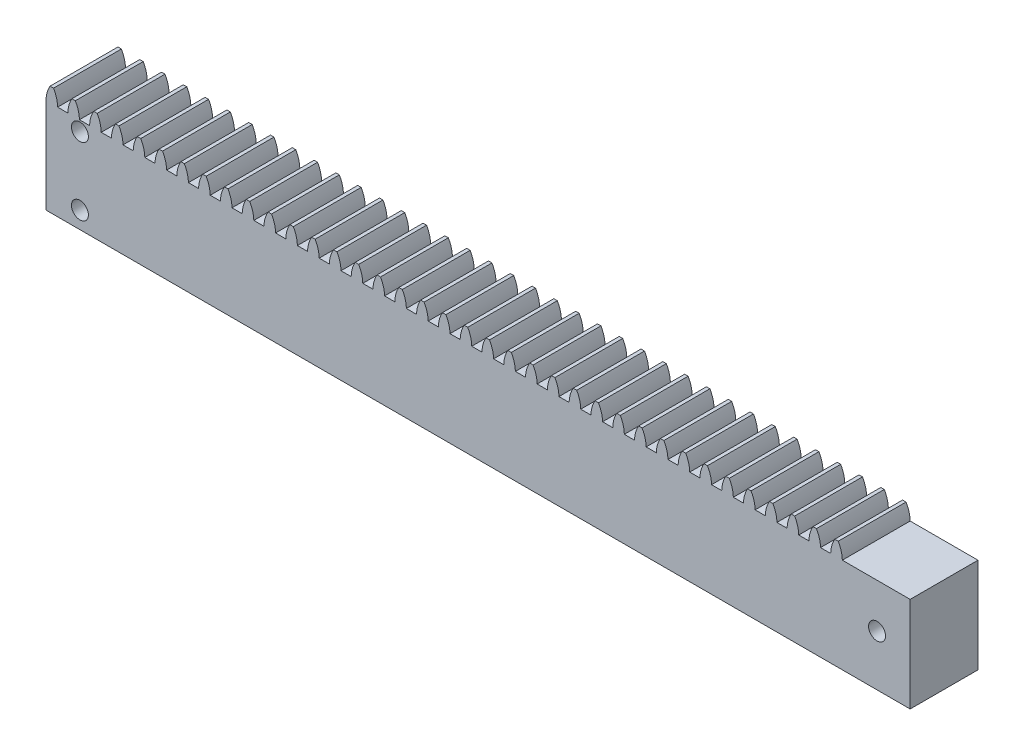
SolidWorks part; units mm, degrees
material "自訂玻璃纖維"
ref_plane "前基準面" through (0, 0, 0) normal (0, 0, 1) x (1, 0, 0)
ref_plane "上基準面" through (0, 0, 0) normal (0, 1, 0) x (1, 0, 0)
ref_plane "右基準面" through (0, 0, 0) normal (1, 0, 0) x (0, 0, -1)
sketch "草圖2" plane through (-38.6801, 0, 0) normal (0, 0, 1) x (1, 0, 0)
  line L0 (1.0493, 17.4015) -> (1.5623, 17.4015)
  line L1 (2.1626, 15.2764) -> (3.6621, 15.2764)
  line L2 (5.3756, 15.2764) -> (6.8752, 15.2764)
  line L3 (4.2623, 17.4015) -> (4.7754, 17.4015)
  line L4 (7.4754, 17.4015) -> (7.9884, 17.4015)
  line L5 (8.5886, 15.2764) -> (10.0882, 15.2764)
  line L6 (11.8017, 15.2764) -> (13.3012, 15.2764)
  line L7 (10.6884, 17.4015) -> (11.2014, 17.4015)
  line L8 (13.9014, 17.4015) -> (14.4145, 17.4015)
  line L9 (15.0147, 15.2764) -> (16.5143, 15.2764)
  line L10 (18.2277, 15.2764) -> (19.7273, 15.2764)
  line L11 (17.1145, 17.4015) -> (17.6275, 17.4015)
  line L12 (20.3275, 17.4015) -> (20.8405, 17.4015)
  line L13 (21.4408, 15.2764) -> (22.9403, 15.2764)
  line L14 (24.6538, 15.2764) -> (26.1534, 15.2764)
  line L15 (23.5405, 17.4015) -> (24.0536, 17.4015)
  line L16 (26.7536, 17.4015) -> (27.2666, 17.4015)
  line L17 (27.8668, 15.2764) -> (29.3664, 15.2764)
  line L18 (31.0799, 15.2764) -> (32.5794, 15.2764)
  line L19 (29.9666, 17.4015) -> (30.4797, 17.4015)
  line L20 (33.1797, 17.4015) -> (33.6927, 17.4015)
  line L21 (34.2929, 15.2764) -> (35.7925, 15.2764)
  line L22 (37.5059, 15.2764) -> (39.0055, 15.2764)
  line L23 (36.3927, 17.4015) -> (36.9057, 17.4015)
  line L24 (39.6057, 17.4015) -> (40.1188, 17.4015)
  line L25 (40.719, 15.2764) -> (42.2185, 15.2764)
  line L26 (43.932, 15.2764) -> (45.4316, 15.2764)
  line L27 (42.8188, 17.4015) -> (43.3318, 17.4015)
  line L28 (46.0318, 17.4015) -> (46.5448, 17.4015)
  line L29 (47.145, 15.2764) -> (48.6446, 15.2764)
  line L30 (50.3581, 15.2764) -> (51.8576, 15.2764)
  line L31 (49.2448, 17.4015) -> (49.7579, 17.4015)
  line L32 (52.4579, 17.4015) -> (52.9709, 17.4015)
  line L33 (53.5711, 15.2764) -> (55.0707, 15.2764)
  line L34 (56.7841, 15.2764) -> (58.2837, 15.2764)
  line L35 (55.6709, 17.4015) -> (56.1839, 17.4015)
  line L36 (58.8839, 17.4015) -> (59.397, 17.4015)
  line L37 (59.9972, 15.2764) -> (61.4967, 15.2764)
  line L38 (63.2102, 15.2764) -> (64.7098, 15.2764)
  line L39 (62.097, 17.4015) -> (62.61, 17.4015)
  line L40 (65.31, 17.4015) -> (65.823, 17.4015)
  line L41 (66.4233, 15.2764) -> (67.9228, 15.2764)
  line L42 (69.6363, 15.2764) -> (71.1358, 15.2764)
  line L43 (68.523, 17.4015) -> (69.0361, 17.4015)
  line L44 (71.7361, 17.4015) -> (72.2491, 17.4015)
  line L45 (72.8493, 15.2764) -> (74.3489, 15.2764)
  line L46 (76.0624, 15.2764) -> (77.5619, 15.2764)
  line L47 (74.9491, 17.4015) -> (75.4621, 17.4015)
  line L48 (78.1621, 17.4015) -> (78.6752, 17.4015)
  line L49 (79.2754, 15.2764) -> (80.7749, 15.2764)
  line L50 (82.4884, 15.2764) -> (83.988, 15.2764)
  line L51 (81.3752, 17.4015) -> (81.8882, 17.4015)
  line L52 (84.5882, 17.4015) -> (85.1012, 17.4015)
  line L53 (85.7015, 15.2764) -> (87.201, 15.2764)
  line L54 (88.9145, 15.2764) -> (90.414, 15.2764)
  line L55 (87.8012, 17.4015) -> (88.3143, 17.4015)
  line L56 (91.0143, 17.4015) -> (91.5273, 17.4015)
  line L57 (92.1275, 15.2764) -> (93.6271, 15.2764)
  line L58 (95.3406, 15.2764) -> (96.8401, 15.2764)
  line L59 (94.2273, 17.4015) -> (94.7403, 17.4015)
  line L60 (97.4403, 17.4015) -> (97.9534, 17.4015)
  line L61 (98.5536, 15.2764) -> (100.0532, 15.2764)
  line L62 (101.7666, 15.2764) -> (103.2662, 15.2764)
  line L63 (100.6534, 17.4015) -> (101.1664, 17.4015)
  line L64 (103.8664, 17.4015) -> (104.3794, 17.4015)
  line L65 (104.9797, 15.2764) -> (106.4792, 15.2764)
  line L66 (108.1927, 15.2764) -> (109.6923, 15.2764)
  line L67 (107.0794, 17.4015) -> (107.5925, 17.4015)
  line L68 (110.2925, 17.4015) -> (110.8055, 17.4015)
  line L69 (111.4057, 15.2764) -> (112.9053, 15.2764)
  line L70 (114.6188, 15.2764) -> (116.1183, 15.2764)
  line L71 (113.5055, 17.4015) -> (114.0185, 17.4015)
  line L72 (116.7185, 17.4015) -> (117.2316, 17.4015)
  line L73 (117.8318, 15.2764) -> (127.8318, 15.2764)
  line L74 (127.8318, 15.2764) -> (127.8318, 1.2764)
  line L75 (127.8318, 1.2764) -> (0.4491, 1.2764)
  line L76 (0.4491, 1.2764) -> (0.4491, 15.2764)
  arc A0 (2.1626, 15.2764) -> (1.5623, 17.4015) centre (-2.2949, 15.1647) ccw
  arc A1 (0.4491, 15.2764) -> (1.0493, 17.4015) centre (4.9065, 15.1647) cw
  arc A2 (5.3756, 15.2764) -> (4.7754, 17.4015) centre (0.9182, 15.1647) ccw
  arc A3 (3.6621, 15.2764) -> (4.2623, 17.4015) centre (8.1195, 15.1647) cw
  arc A4 (10.0882, 15.2764) -> (10.6884, 17.4015) centre (14.5456, 15.1647) cw
  arc A5 (8.5886, 15.2764) -> (7.9884, 17.4015) centre (4.1312, 15.1647) ccw
  arc A6 (6.8752, 15.2764) -> (7.4754, 17.4015) centre (11.3326, 15.1647) cw
  arc A7 (11.8017, 15.2764) -> (11.2014, 17.4015) centre (7.3442, 15.1647) ccw
  arc A8 (16.5143, 15.2764) -> (17.1145, 17.4015) centre (20.9717, 15.1647) cw
  arc A9 (15.0147, 15.2764) -> (14.4145, 17.4015) centre (10.5573, 15.1647) ccw
  arc A10 (13.3012, 15.2764) -> (13.9014, 17.4015) centre (17.7587, 15.1647) cw
  arc A11 (18.2277, 15.2764) -> (17.6275, 17.4015) centre (13.7703, 15.1647) ccw
  arc A12 (22.9403, 15.2764) -> (23.5405, 17.4015) centre (27.3978, 15.1647) cw
  arc A13 (21.4408, 15.2764) -> (20.8405, 17.4015) centre (16.9833, 15.1647) ccw
  arc A14 (19.7273, 15.2764) -> (20.3275, 17.4015) centre (24.1847, 15.1647) cw
  arc A15 (24.6538, 15.2764) -> (24.0536, 17.4015) centre (20.1964, 15.1647) ccw
  arc A16 (29.3664, 15.2764) -> (29.9666, 17.4015) centre (33.8238, 15.1647) cw
  arc A17 (27.8668, 15.2764) -> (27.2666, 17.4015) centre (23.4094, 15.1647) ccw
  arc A18 (26.1534, 15.2764) -> (26.7536, 17.4015) centre (30.6108, 15.1647) cw
  arc A19 (31.0799, 15.2764) -> (30.4797, 17.4015) centre (26.6224, 15.1647) ccw
  arc A20 (35.7925, 15.2764) -> (36.3927, 17.4015) centre (40.2499, 15.1647) cw
  arc A21 (34.2929, 15.2764) -> (33.6927, 17.4015) centre (29.8355, 15.1647) ccw
  arc A22 (32.5794, 15.2764) -> (33.1797, 17.4015) centre (37.0369, 15.1647) cw
  arc A23 (37.5059, 15.2764) -> (36.9057, 17.4015) centre (33.0485, 15.1647) ccw
  arc A24 (42.2185, 15.2764) -> (42.8188, 17.4015) centre (46.676, 15.1647) cw
  arc A25 (40.719, 15.2764) -> (40.1188, 17.4015) centre (36.2615, 15.1647) ccw
  arc A26 (39.0055, 15.2764) -> (39.6057, 17.4015) centre (43.4629, 15.1647) cw
  arc A27 (43.932, 15.2764) -> (43.3318, 17.4015) centre (39.4746, 15.1647) ccw
  arc A28 (48.6446, 15.2764) -> (49.2448, 17.4015) centre (53.102, 15.1647) cw
  arc A29 (47.145, 15.2764) -> (46.5448, 17.4015) centre (42.6876, 15.1647) ccw
  arc A30 (45.4316, 15.2764) -> (46.0318, 17.4015) centre (49.889, 15.1647) cw
  arc A31 (50.3581, 15.2764) -> (49.7579, 17.4015) centre (45.9007, 15.1647) ccw
  arc A32 (55.0707, 15.2764) -> (55.6709, 17.4015) centre (59.5281, 15.1647) cw
  arc A33 (53.5711, 15.2764) -> (52.9709, 17.4015) centre (49.1137, 15.1647) ccw
  arc A34 (51.8576, 15.2764) -> (52.4579, 17.4015) centre (56.3151, 15.1647) cw
  arc A35 (56.7841, 15.2764) -> (56.1839, 17.4015) centre (52.3267, 15.1647) ccw
  arc A36 (61.4967, 15.2764) -> (62.097, 17.4015) centre (65.9542, 15.1647) cw
  arc A37 (59.9972, 15.2764) -> (59.397, 17.4015) centre (55.5398, 15.1647) ccw
  arc A38 (58.2837, 15.2764) -> (58.8839, 17.4015) centre (62.7411, 15.1647) cw
  arc A39 (63.2102, 15.2764) -> (62.61, 17.4015) centre (58.7528, 15.1647) ccw
  arc A40 (67.9228, 15.2764) -> (68.523, 17.4015) centre (72.3802, 15.1647) cw
  arc A41 (66.4233, 15.2764) -> (65.823, 17.4015) centre (61.9658, 15.1647) ccw
  arc A42 (64.7098, 15.2764) -> (65.31, 17.4015) centre (69.1672, 15.1647) cw
  arc A43 (69.6363, 15.2764) -> (69.0361, 17.4015) centre (65.1789, 15.1647) ccw
  arc A44 (74.3489, 15.2764) -> (74.9491, 17.4015) centre (78.8063, 15.1647) cw
  arc A45 (72.8493, 15.2764) -> (72.2491, 17.4015) centre (68.3919, 15.1647) ccw
  arc A46 (71.1358, 15.2764) -> (71.7361, 17.4015) centre (75.5933, 15.1647) cw
  arc A47 (76.0624, 15.2764) -> (75.4621, 17.4015) centre (71.6049, 15.1647) ccw
  arc A48 (80.7749, 15.2764) -> (81.3752, 17.4015) centre (85.2324, 15.1647) cw
  arc A49 (79.2754, 15.2764) -> (78.6752, 17.4015) centre (74.818, 15.1647) ccw
  arc A50 (77.5619, 15.2764) -> (78.1621, 17.4015) centre (82.0193, 15.1647) cw
  arc A51 (82.4884, 15.2764) -> (81.8882, 17.4015) centre (78.031, 15.1647) ccw
  arc A52 (87.201, 15.2764) -> (87.8012, 17.4015) centre (91.6584, 15.1647) cw
  arc A53 (85.7015, 15.2764) -> (85.1012, 17.4015) centre (81.244, 15.1647) ccw
  arc A54 (83.988, 15.2764) -> (84.5882, 17.4015) centre (88.4454, 15.1647) cw
  arc A55 (88.9145, 15.2764) -> (88.3143, 17.4015) centre (84.4571, 15.1647) ccw
  arc A56 (93.6271, 15.2764) -> (94.2273, 17.4015) centre (98.0845, 15.1647) cw
  arc A57 (92.1275, 15.2764) -> (91.5273, 17.4015) centre (87.6701, 15.1647) ccw
  arc A58 (90.414, 15.2764) -> (91.0143, 17.4015) centre (94.8715, 15.1647) cw
  arc A59 (95.3406, 15.2764) -> (94.7403, 17.4015) centre (90.8831, 15.1647) ccw
  arc A60 (100.0532, 15.2764) -> (100.6534, 17.4015) centre (104.5106, 15.1647) cw
  arc A61 (98.5536, 15.2764) -> (97.9534, 17.4015) centre (94.0962, 15.1647) ccw
  arc A62 (96.8401, 15.2764) -> (97.4403, 17.4015) centre (101.2975, 15.1647) cw
  arc A63 (101.7666, 15.2764) -> (101.1664, 17.4015) centre (97.3092, 15.1647) ccw
  arc A64 (106.4792, 15.2764) -> (107.0794, 17.4015) centre (110.9366, 15.1647) cw
  arc A65 (104.9797, 15.2764) -> (104.3794, 17.4015) centre (100.5222, 15.1647) ccw
  arc A66 (103.2662, 15.2764) -> (103.8664, 17.4015) centre (107.7236, 15.1647) cw
  arc A67 (108.1927, 15.2764) -> (107.5925, 17.4015) centre (103.7353, 15.1647) ccw
  arc A68 (112.9053, 15.2764) -> (113.5055, 17.4015) centre (117.3627, 15.1647) cw
  arc A69 (111.4057, 15.2764) -> (110.8055, 17.4015) centre (106.9483, 15.1647) ccw
  arc A70 (109.6923, 15.2764) -> (110.2925, 17.4015) centre (114.1497, 15.1647) cw
  arc A71 (114.6188, 15.2764) -> (114.0185, 17.4015) centre (110.1613, 15.1647) ccw
  arc A73 (117.8318, 15.2764) -> (117.2316, 17.4015) centre (113.3744, 15.1647) ccw
  arc A74 (116.1183, 15.2764) -> (116.7185, 17.4015) centre (120.5758, 15.1647) cw
  point P18 (1.0493, 17.4015)
  point P19 (1.5623, 17.4015)
  point P20 (0.4491, 15.2764)
  point P21 (2.1626, 15.2764)
  point P22 (127.8318, 15.2764)
  point P31 (7.4754, 17.4015)
  point P32 (7.9884, 17.4015)
  point P33 (6.8752, 15.2764)
  point P34 (8.5886, 15.2764)
  point P48 (13.9014, 17.4015)
  point P49 (14.4145, 17.4015)
  point P50 (13.3012, 15.2764)
  point P51 (15.0147, 15.2764)
  point P65 (20.3275, 17.4015)
  point P66 (20.8405, 17.4015)
  point P67 (19.7273, 15.2764)
  point P68 (21.4408, 15.2764)
  point P82 (26.7536, 17.4015)
  point P83 (27.2666, 17.4015)
  point P84 (26.1534, 15.2764)
  point P85 (27.8668, 15.2764)
  point P99 (33.1797, 17.4015)
  point P100 (33.6927, 17.4015)
  point P101 (32.5794, 15.2764)
  point P102 (34.2929, 15.2764)
  point P116 (39.6057, 17.4015)
  point P117 (40.1188, 17.4015)
  point P118 (39.0055, 15.2764)
  point P119 (40.719, 15.2764)
  point P133 (46.0318, 17.4015)
  point P134 (46.5448, 17.4015)
  point P135 (45.4316, 15.2764)
  point P136 (47.145, 15.2764)
  point P150 (52.4579, 17.4015)
  point P151 (52.9709, 17.4015)
  point P152 (51.8576, 15.2764)
  point P153 (53.5711, 15.2764)
  point P167 (58.8839, 17.4015)
  point P168 (59.397, 17.4015)
  point P169 (58.2837, 15.2764)
  point P170 (59.9972, 15.2764)
  point P184 (65.31, 17.4015)
  point P185 (65.823, 17.4015)
  point P186 (64.7098, 15.2764)
  point P187 (66.4233, 15.2764)
  point P201 (71.7361, 17.4015)
  point P202 (72.2491, 17.4015)
  point P203 (71.1358, 15.2764)
  point P204 (72.8493, 15.2764)
  point P218 (78.1621, 17.4015)
  point P219 (78.6752, 17.4015)
  point P220 (77.5619, 15.2764)
  point P221 (79.2754, 15.2764)
  point P235 (84.5882, 17.4015)
  point P236 (85.1012, 17.4015)
  point P237 (83.988, 15.2764)
  point P238 (85.7015, 15.2764)
  point P252 (91.0143, 17.4015)
  point P253 (91.5273, 17.4015)
  point P254 (90.414, 15.2764)
  point P255 (92.1275, 15.2764)
  point P269 (97.4403, 17.4015)
  point P270 (97.9534, 17.4015)
  point P271 (96.8401, 15.2764)
  point P272 (98.5536, 15.2764)
  point P286 (103.8664, 17.4015)
  point P287 (104.3794, 17.4015)
  point P288 (103.2662, 15.2764)
  point P289 (104.9797, 15.2764)
  point P303 (110.2925, 17.4015)
  point P304 (110.8055, 17.4015)
  point P305 (109.6923, 15.2764)
  point P306 (111.4057, 15.2764)
  point P320 (116.7185, 17.4015)
  point P321 (117.2316, 17.4015)
  point P322 (116.1183, 15.2764)
  point P323 (117.8318, 15.2764)
  dimension "D1" = 14
  dimension "D2" = 2.7
  dimension "D3" = 10
extrude "填料-伸長3" add sketch "草圖2" along normal blind 10
sketch "草圖3" plane through (0, 0, 10) normal (0, 0, 1) x (1, 0, 0)
  line L0 (-38.231, 1.2764) -> (89.1517, 1.2764) construction
  line L1 (-38.231, 15.2764) -> (-38.231, 1.2764) construction
  circle A0 centre (-33.231, 13.7764) radius 1.25
  circle A1 centre (-33.231, 3.7764) radius 1.25
  circle A2 centre (84.269, 8.7764) radius 1.25
  dimension "D1" = 10
  dimension "D2" = 2.5
  dimension "D3" = 2.5
  dimension "D4" = 5
  dimension "D5" = 5
  dimension "D6" = 2.5
  dimension "D7" = 7.5
  dimension "D8" = 117.5
extrude "除料-伸長1" cut sketch "草圖3" against normal blind 10
